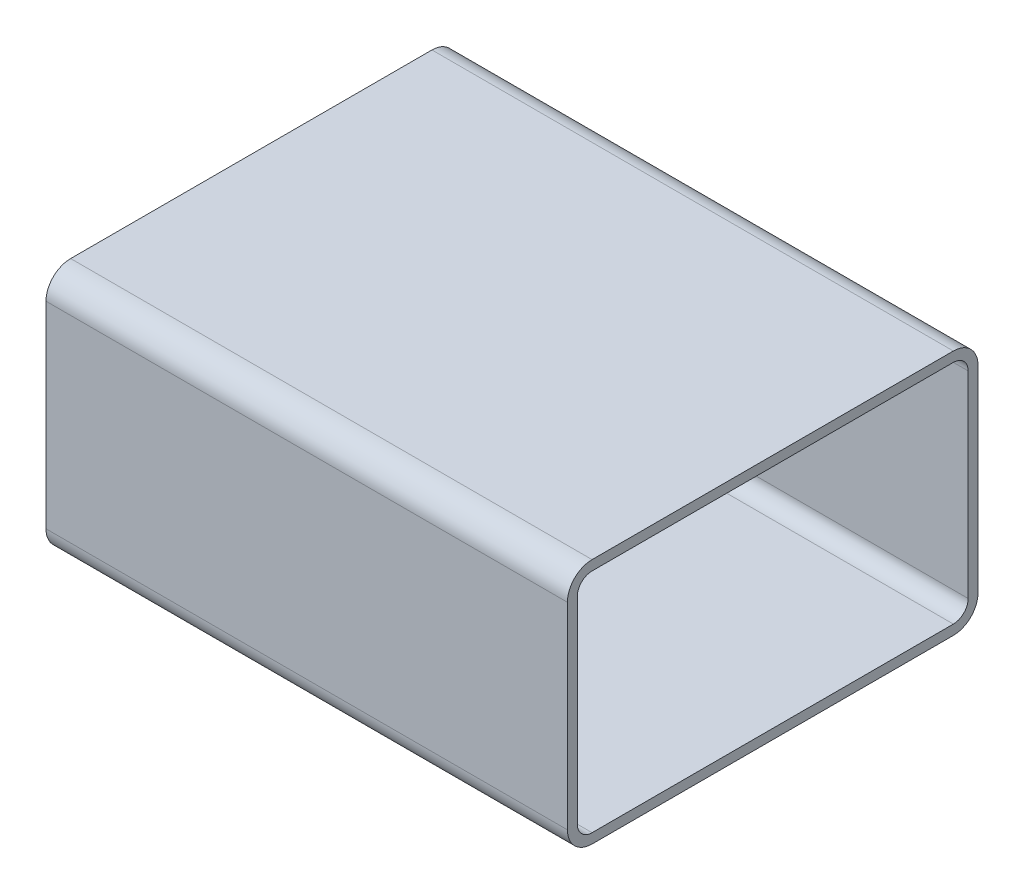
SolidWorks part; units mm, degrees
material "AISI 304"
ref_plane "Plano frontal" through (0, 0, 0) normal (0, 0, 1) x (1, 0, 0)
ref_plane "Plano superior" through (0, 0, 0) normal (0, 1, 0) x (1, 0, 0)
ref_plane "Plano direito" through (0, 0, 0) normal (1, 0, 0) x (0, 0, -1)
sketch "Esboço1" plane through (0, 0, 0) normal (0, 0, 1) x (1, 0, 0)
  line L0 (0, 0) -> (63.5, 0)
  dimension "D1" = 63.5
other "Tubo retangular 50 X 30 X 2.6(1)"
ref_plane "Plano1" through (0, 0, 0) normal (1, 0, 0) x (0, 1, 0)
sketch "Sketch1" plane through (0, 0, 0) normal (1, 0, 0) x (0, 1, 0)
  line L0 (-12, -23.8) -> (12, -23.8)
  line L1 (-13.8, -22) -> (-13.8, 22)
  line L2 (12, 23.8) -> (-12, 23.8)
  line L3 (13.8, 22) -> (13.8, -22)
  line L4 (-12, -25) -> (12, -25)
  line L5 (-15, -22) -> (-15, 22)
  line L6 (12, 25) -> (-12, 25)
  line L7 (15, 22) -> (15, -22)
  arc A0 (15, 22) -> (12, 25) centre (12, 22) ccw
  arc A1 (12, -25) -> (15, -22) centre (12, -22) ccw
  arc A2 (-15, -22) -> (-12, -25) centre (-12, -22) ccw
  arc A3 (-12, 25) -> (-15, 22) centre (-12, 22) ccw
  arc A4 (-12, 23.8) -> (-13.8, 22) centre (-12, 22) ccw
  arc A5 (13.8, 22) -> (12, 23.8) centre (12, 22) ccw
  arc A6 (12, -23.8) -> (13.8, -22) centre (12, -22) ccw
  arc A7 (-13.8, -22) -> (-12, -23.8) centre (-12, -22) ccw
  point P0 (0, 25)
  point P1 (15, 0)
  point P2 (0, -25)
  point P3 (-15, 0)
  point P4 (-15, 25)
  point P5 (15, 25)
  point P6 (15, -25)
  point P7 (-15, -25)
  point P8 (0, 0)
  point P33 (0, 0)
  dimension "D1" = 3
  dimension "Thickness" = 1.2
  dimension "V_leg" = 50
  dimension "H_leg" = 30
